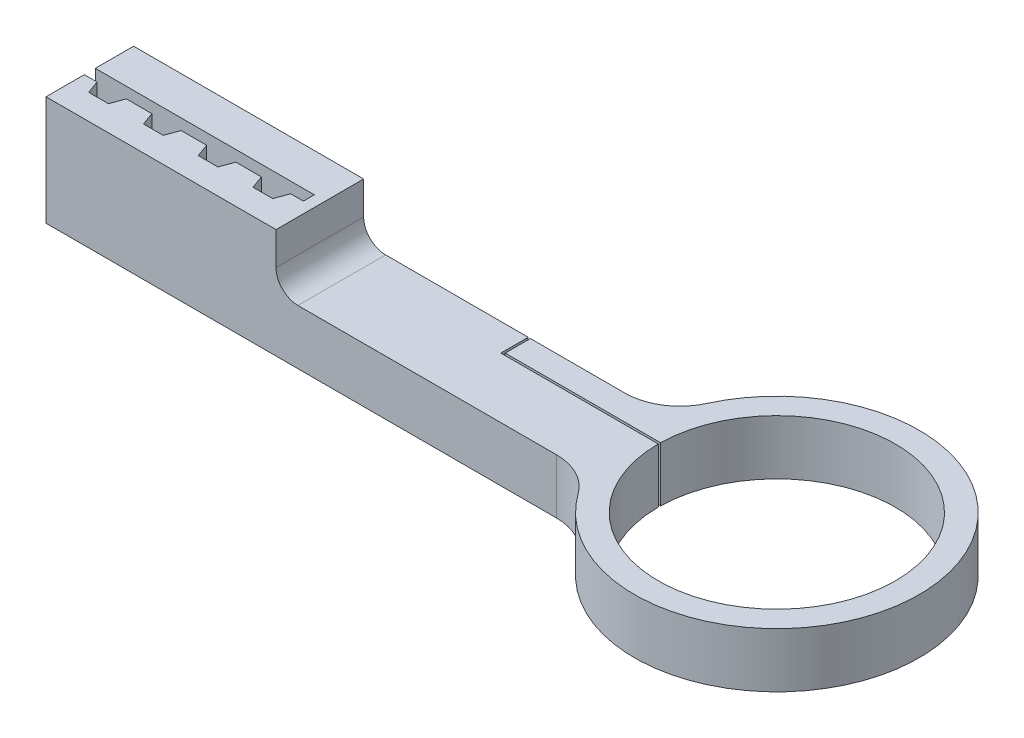
SolidWorks part; units mm, degrees
ref_plane "Спереди" through (0, 0, 0) normal (0, 0, 1) x (1, 0, 0)
ref_plane "Сверху" through (0, 0, 0) normal (0, 1, 0) x (1, 0, 0)
ref_plane "Справа" through (0, 0, 0) normal (1, 0, 0) x (0, 0, -1)
sketch "Эскиз1" plane through (0, 0, 0) normal (0, 1, 0) x (1, 0, 0)
  circle A0 centre (0, 0) radius 10.825
  circle A1 centre (0, 0) radius 13
  dimension "D1" = 21.65
  dimension "D2" = 26
extrude "ring" add sketch "Эскиз1" along normal blind 5
sketch "Эскиз2" plane through (0, 0, 0) normal (0, 1, 0) x (1, 0, 0)
  line L0 (34.0214, 0) -> (-42.1067, 0) construction
  line L2 (-11.225, 2.5) -> (-61.225, 2.5)
  line L3 (-11.225, 2.5) -> (-11.225, -5.5)
  line L4 (-11.225, -5.5) -> (-61.225, -5.5)
  line L5 (-61.225, 2.5) -> (-61.225, -5.5)
  circle A0 centre (0, 0) radius 11.5 construction
  dimension "D3" = 23
  dimension "D1" = 2.5
  dimension "D2" = 8
  dimension "D4" = 50
extrude "stick" add sketch "Эскиз2" along normal blind 5
sketch "Эскиз3" plane through (0, 0, 0) normal (0, 1, 0) x (1, 0, 0)
  line L0 (-61.225, -5.5) -> (-11.7792, -5.5) construction
  line L1 (-61.225, 2.5) -> (-40.225, 2.5)
  line L2 (-61.225, 2.5) -> (-61.225, -5.5)
  line L3 (-61.225, -5.5) -> (-40.225, -5.5)
  line L4 (-40.225, 2.5) -> (-40.225, -5.5)
  dimension "D1" = 21
extrude "key" add sketch "Эскиз3" along normal blind 10
fillet "Скругление1" radius 5 2 edges at (-11.7792, 2.5, 5.5) (-12.7574, 2.5, -2.5)
ref_plane "Плоскость1" through (0, 2.5, 0) normal (0, 1, 0) x (-1, 0, 0)
sketch "Эскиз4" plane through (0, 2.5, 0) normal (0, 1, 0) x (1, 0, 0)
  line L0 (-61.225, -1.5) -> (-40.225, -1.5) construction
  line L1 (-61.225, 2.5) -> (-61.225, -5.5) construction
  line L2 (-40.225, -5.5) -> (-40.225, 2.5) construction
  line L3 (-61.225, -1) -> (-41.225, -1)
  line L4 (-59.625, -3.2) -> (-57.825, -3.2)
  line L5 (-60.0617, -2) -> (-41.2194, -2) construction
  line L6 (-60.0617, -2) -> (-59.625, -3.2) construction
  line L7 (-60.0617, -2) -> (-59.625, -3.2)
  line L8 (-57.825, -3.2) -> (-57.3882, -2)
  line L9 (-58.725, -0.4843) -> (-58.725, -4.9603) construction
  line L10 (-60.0617, -2) -> (-61.225, -2)
  line L11 (-57.3882, -2) -> (-56.225, -2)
  line L12 (-61.225, -1) -> (-61.225, -2)
  line L13 (-55.0617, -2) -> (-56.225, -2)
  line L14 (-55.0617, -2) -> (-54.625, -3.2)
  line L15 (-54.625, -3.2) -> (-52.825, -3.2)
  line L16 (-52.825, -3.2) -> (-52.3882, -2)
  line L17 (-52.3882, -2) -> (-51.225, -2)
  line L18 (-50.0617, -2) -> (-51.225, -2)
  line L19 (-50.0617, -2) -> (-49.625, -3.2)
  line L20 (-49.625, -3.2) -> (-47.825, -3.2)
  line L21 (-47.825, -3.2) -> (-47.3882, -2)
  line L22 (-47.3882, -2) -> (-46.225, -2)
  line L23 (-45.0617, -2) -> (-46.225, -2)
  line L24 (-45.0617, -2) -> (-44.625, -3.2)
  line L25 (-44.625, -3.2) -> (-42.825, -3.2)
  line L26 (-42.825, -3.2) -> (-42.3882, -2)
  line L27 (-42.3882, -2) -> (-41.225, -2)
  line L28 (-41.225, -1) -> (-41.225, -2)
  point P12 (-58.725, -3.2)
  dimension "D1" = 1.8
  dimension "D2" = 0.5
  dimension "D3" = 0.5
  dimension "D4" = 1.2
  dimension "D5" = 110
  dimension "D6" = 5
  dimension "D7" = 40
fillet "Скругление5" radius 2 1 edges at (-40.225, 5, 1.5)
extrude "key hole" cut sketch "Эскиз4" against normal through all and the other way through all
sketch "Эскиз5" plane through (0, 0, 0) normal (0, -1, 0) x (1, 0, 0)
  line L0 (0, 0) -> (-70.3859, 0) construction
  line L1 (-25.2, -2.5) -> (-25.2, 0)
  line L3 (-25.2, 0) -> (0, 0)
  line L4 (0, 0) -> (0, -0.2)
  line L5 (0, -0.2) -> (-25, -0.2)
  line L6 (-25, -0.2) -> (-25, -2.5)
  line L7 (-25, -2.5) -> (-25.2, -2.5)
  line L8 (-16.3631, -2.5) -> (-61.225, -2.5) construction
  dimension "D1" = 0.2
  dimension "D2" = 0.2
  dimension "D3" = 25
extrude "Вытянуть2" cut sketch "Эскиз5" against normal through all
